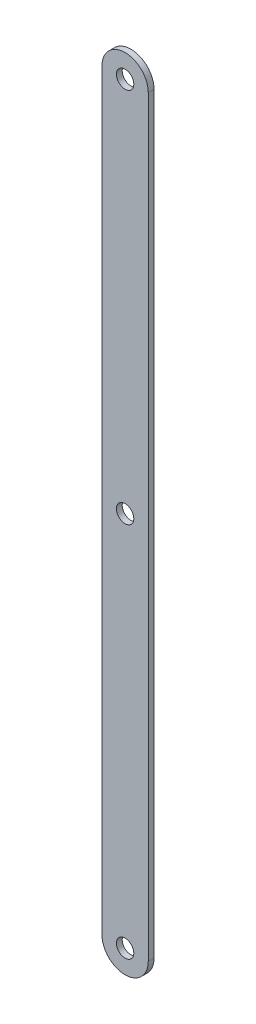
SolidWorks part; units mm, degrees
ref_plane "Front Plane" through (0, 0, 0) normal (0, 0, 1) x (1, 0, 0)
ref_plane "Top Plane" through (0, 0, 0) normal (0, 1, 0) x (1, 0, 0)
ref_plane "Right Plane" through (0, 0, 0) normal (1, 0, 0) x (0, 0, -1)
sketch "Sketch1" plane through (0, 0, 0) normal (0, 0, 1) x (1, 0, 0)
  line L0 (0, 0) -> (0, 650) construction
  line L1 (-20, 0) -> (-20, 650)
  line L2 (20, 0) -> (20, 650)
  arc A0 (-20, 0) -> (20, 0) centre (0, 0) ccw
  arc A1 (20, 650) -> (-20, 650) centre (0, 650) ccw
  circle A2 centre (0, 650) radius 7.5
  circle A3 centre (0, 0) radius 7.5
  circle A4 centre (0, 325) radius 7.5
  point P3 (0, 325)
  dimension "D2" = 20
  dimension "D3" = 15
  dimension "D4" = 15
  dimension "D5" = 15
  dimension "D1" = 650
extrude "Boss-Extrude1" add sketch "Sketch1" along normal blind 5
